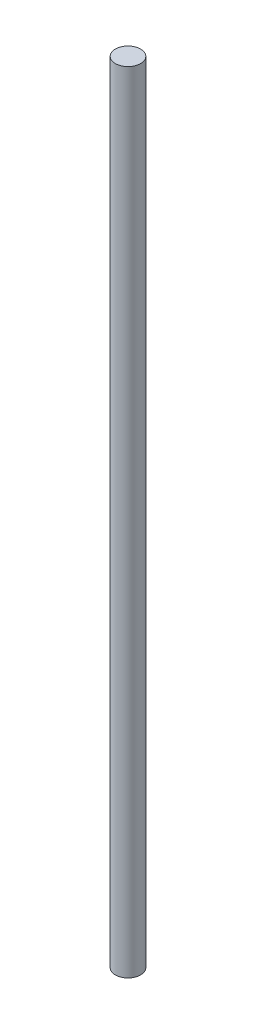
SolidWorks part; units mm, degrees
ref_plane "Front Plane" through (0, 0, 0) normal (0, 0, 1) x (1, 0, 0)
ref_plane "Top Plane" through (0, 0, 0) normal (0, 1, 0) x (1, 0, 0)
ref_plane "Right Plane" through (0, 0, 0) normal (1, 0, 0) x (0, 0, -1)
sketch "Sketch1" plane through (0, 0, 0) normal (0, 1, 0) x (1, 0, 0)
  circle A0 centre (0, 0) radius 0.575
  dimension "D1" = 1.15
extrude "Boss-Extrude1" add sketch "Sketch1" along normal blind 36
